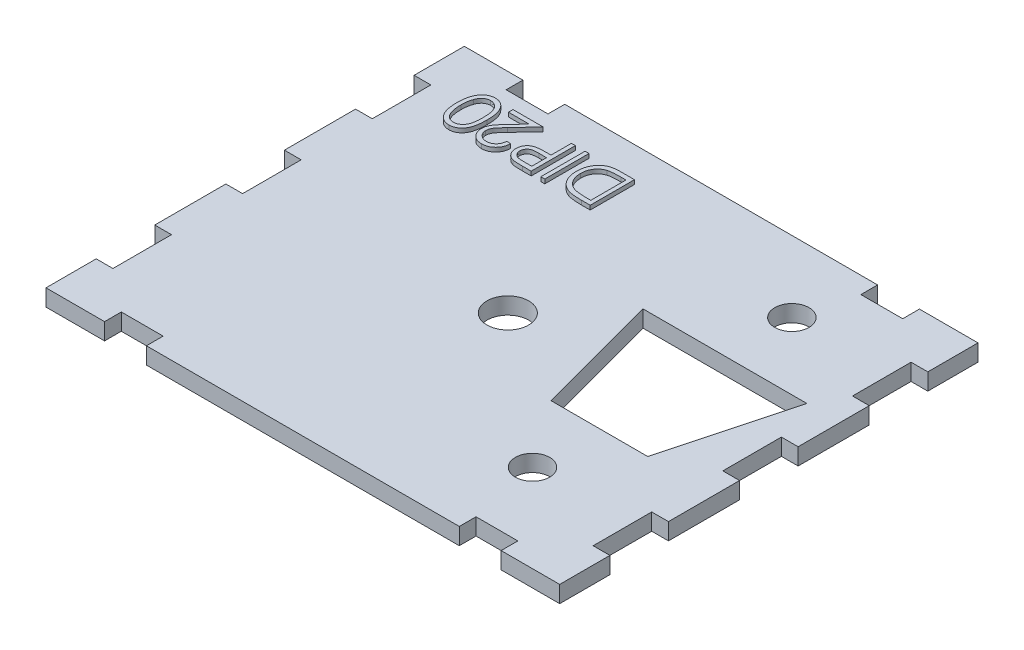
SolidWorks part; units mm, degrees
ref_plane "Front Plane" through (0, 0, 0) normal (0, 0, 1) x (1, 0, 0)
ref_plane "Top Plane" through (0, 0, 0) normal (0, 1, 0) x (1, 0, 0)
ref_plane "Right Plane" through (0, 0, 0) normal (1, 0, 0) x (0, 0, -1)
sketch "Sketch2" plane through (0, 0, 0) normal (0, 1, 0) x (1, 0, 0)
  line L1 (-50, 25) -> (50, 25)
  line L2 (-50, 25) -> (-50, -25)
  line L3 (-50, -25) -> (50, -25)
  line L4 (50, 25) -> (50, -25)
  line L5 (-50, 25) -> (50, -25) construction
  line L6 (-50, -25) -> (50, 25) construction
  point P0 (0, 0)
  dimension "D1" = 100
  dimension "D2" = 50
extrude "Boss-Extrude1" add sketch "Sketch2" along normal blind 2
sketch "Sketch12" plane through (0, 2, 0) normal (0, 1, 0) x (1, 0, 0)
  line L0 (-50, -25) -> (50, -25) construction
  line L1 (-40.2, -25) -> (-50, -25)
  line L2 (-40.2, -25) -> (-40.2, 25)
  line L3 (-40.2, 25) -> (-50, 25)
  line L4 (-50, -25) -> (-50, 25)
  line L5 (-50, -25) -> (50, -25) construction
  line L6 (41.2, -25) -> (50, -25)
  line L7 (41.2, -25) -> (41.2, 25)
  line L8 (41.2, 25) -> (50, 25)
  line L9 (50, -25) -> (50, 25)
extrude "Cut-Extrude8" cut sketch "Sketch12" against normal blind 6
sketch "Sketch13" plane through (0, 2, 0) normal (0, 1, 0) x (1, 0, 0)
  line L1 (-28.2, 19) -> (-30.2, 19)
  line L2 (-28.2, 19) -> (-28.2, 12)
  line L3 (-28.2, 12) -> (-30.2, 12)
  line L4 (-30.2, 19) -> (-30.2, 12)
  line L5 (-28.2, 3.5) -> (-30.2, 3.5)
  line L6 (-28.2, 3.5) -> (-28.2, -3.5)
  line L7 (-28.2, -3.5) -> (-30.2, -3.5)
  line L8 (-30.2, 3.5) -> (-30.2, -3.5)
  line L9 (-28.2, -12) -> (-30.2, -12)
  line L10 (-28.2, -12) -> (-28.2, -19)
  line L11 (-28.2, -19) -> (-30.2, -19)
  line L12 (-30.2, -12) -> (-30.2, -19)
  line L13 (29.2, 19) -> (31.2, 19)
  line L14 (29.2, 19) -> (29.2, 12)
  line L15 (29.2, 12) -> (31.2, 12)
  line L16 (31.2, 19) -> (31.2, 12)
  line L17 (29.2, 3.5) -> (31.2, 3.5)
  line L18 (29.2, 3.5) -> (29.2, -3.5)
  line L19 (29.2, -3.5) -> (31.2, -3.5)
  line L20 (31.2, 3.5) -> (31.2, -3.5)
  line L21 (29.2, -12) -> (31.2, -12)
  line L22 (29.2, -12) -> (29.2, -19)
  line L23 (29.2, -19) -> (31.2, -19)
  line L24 (31.2, -12) -> (31.2, -19)
  line L25 (-40.2, -25) -> (41.2, -25) construction
  line L26 (-23.2, 25) -> (-18.2, 25)
  line L27 (41.2, 25) -> (-40.2, 25) construction
  line L28 (-40.2, -25) -> (41.2, -25) construction
  line L29 (41.2, 25) -> (-40.2, 25) construction
  line L30 (-40.2, -25) -> (41.2, -25) construction
  line L31 (41.2, 25) -> (31.2, 25)
  line L32 (41.2, 25) -> (41.2, -25)
  line L33 (41.2, -25) -> (31.2, -25)
  line L34 (31.2, 25) -> (31.2, -25)
  line L35 (41.2, 25) -> (-40.2, 25) construction
  line L36 (-40.2, -25) -> (-30.2, -25)
  line L37 (-40.2, -25) -> (-40.2, 25)
  line L38 (-40.2, 25) -> (-30.2, 25)
  line L39 (-30.2, -25) -> (-30.2, 25)
  line L40 (-23.2, 25) -> (-23.2, 23)
  line L41 (-23.2, 23) -> (-18.2, 23)
  line L42 (-18.2, 25) -> (-18.2, 23)
  line L43 (-23.2, -25) -> (-18.2, -25)
  line L44 (-23.2, -25) -> (-23.2, -23)
  line L45 (-23.2, -23) -> (-18.2, -23)
  line L46 (-18.2, -25) -> (-18.2, -23)
  line L47 (24.2, -25) -> (19.2, -25)
  line L48 (24.2, -25) -> (24.2, -23)
  line L49 (24.2, -23) -> (19.2, -23)
  line L50 (19.2, -25) -> (19.2, -23)
  line L51 (24.2, 25) -> (19.2, 25)
  line L52 (24.2, 25) -> (24.2, 23)
  line L53 (24.2, 23) -> (19.2, 23)
  line L54 (19.2, 25) -> (19.2, 23)
  point P24 (29.2, 0)
  point P30 (30.2, 3.5)
  line M32 (41.2, -25) -> (41.2, 25)
  line M41 (41.2, 25) -> (-40.2, 25)
  line M42 (-40.2, 25) -> (-40.2, -25)
  line M47 (-40.2, -25) -> (41.2, -25)
  dimension "D1" = 2
  dimension "D2" = 2
  dimension "D3" = 2
  dimension "D4" = 2
  dimension "D5" = 2
  dimension "D6" = 2
  dimension "D7" = 57.4
  dimension "D8" = 57.4
  dimension "D9" = 57.4
  dimension "D10" = 7
  dimension "D11" = 7
  dimension "D12" = 7
  dimension "D13" = 7
  dimension "D14" = 7
  dimension "D15" = 7
  dimension "D16" = 5
  dimension "D17" = 2
  dimension "D18" = 5
  dimension "D19" = 6
  dimension "D20" = 8.5
  dimension "D21" = 8.5
  dimension "D22" = 6
  dimension "D23" = 6
  dimension "D24" = 8.5
  dimension "D25" = 8.5
  dimension "D26" = 6
  dimension "D27" = 5
  dimension "D28" = 5
  dimension "D29" = 2
  dimension "D30" = 2
  dimension "D31" = 5
  dimension "D32" = 5
  dimension "D33" = 5
  dimension "D34" = 5
  dimension "D35" = 2
extrude "Cut-Extrude10" cut sketch "Sketch13" against normal blind 6 contours L5 L8 L7 L6 | L39 L12 L8 L4 M47 M41 M42 | L1 L4 L3 L2 | L50 L48 L49 M47 | L24 L21 L22 L23 | L20 L17 L18 L19 | L16 L13 L14 L15 | L54 L53 L52 M41 | L9 L12 L11 L10 | L34 L16 L20 L24 M41 M47 M32 | L26 L42 L41 L40 | L45 L46 L43 L44
sketch "Sketch15" plane through (0, 0, 0) normal (0, -1, 0) x (1, 0, 0)
  line L0 (24.2, 23) -> (19.2, 23) construction
  line L16 (20.7242, -7.5) -> (20.7242, -8.5)
  line L17 (20.7242, -7.5) -> (25.936, -7.5)
  line L18 (25.936, -7.5) -> (22.4527, 5.5)
  line L19 (22.4527, 5.5) -> (12.4527, 5.5)
  line L20 (12.4527, 5.5) -> (8.9693, -7.5)
  line L21 (8.9693, -7.5) -> (14.1811, -7.5)
  line L22 (14.1811, -7.5) -> (14.1811, -8.5)
  line L23 (14.1811, -8.5) -> (7.6661, -8.5)
  line L24 (7.6661, -8.5) -> (11.6853, 6.5)
  line L25 (11.6853, 6.5) -> (23.22, 6.5)
  line L26 (23.22, 6.5) -> (27.2392, -8.5)
  line L27 (27.2392, -8.5) -> (20.7242, -8.5)
  line L28 (20.7242, -8.5) -> (14.1811, -8.5)
  line L29 (14.1811, -7.5) -> (20.7242, -7.5)
  line L31 (29.2, 12) -> (29.2, 19) construction
  dimension "D4" = 16.5
  dimension "D18" = 11.5347
  dimension "D19" = 15.5291
  dimension "D20" = 15.5291
  dimension "D21" = 13.4586
  dimension "D22" = 13.4586
  dimension "D23" = 10
  dimension "D24" = 5.2118
  dimension "D25" = 5.2118
  dimension "D26" = 6.515
  dimension "D27" = 6.515
  dimension "D28" = 1
  dimension "D29" = 105
  dimension "D30" = 105
  dimension "D31" = 75
  dimension "D32" = 75
  dimension "D33" = 5.98
  dimension "D34" = 1
extrude "Cut-Extrude13" cut sketch "Sketch15" against normal blind 10 contours L21 L29 L17 L18 L19 L20 | L27 L26 L25 L24 L23 L22 L21 L20 L19 L18 L17 L16 | L29 L22 L28 L16
sketch "Sketch16" plane through (0, 0, 0) normal (0, -1, 0) x (-1, 0, 0)
  circle A0 centre (0, 0) radius 2.5
  dimension "D1" = 5
extrude "Cut-Extrude14" cut sketch "Sketch16" against normal blind 10 contours A0
sketch "Sketch17" plane through (0, 0, 0) normal (0, -1, 0) x (-1, 0, 0)
  line L2 (-27.2392, 8.5) -> (-7.6661, 8.5) construction
  line L4 (-11.6853, -6.5) -> (-23.22, -6.5) construction
  circle A0 centre (-17.4527, -14.5) radius 2.05
  circle A1 centre (-17.4527, 16.5) radius 2.05
  dimension "D1" = 4.1
  dimension "D2" = 4.1
  dimension "D3" = 8
  dimension "D4" = 9.7866
  dimension "D5" = 9.7866
  dimension "D6" = 5.7673
  dimension "D7" = 5.7673
  dimension "D8" = 8
extrude "Cut-Extrude15" cut sketch "Sketch17" against normal blind 3.5
sketch "Sketch22" plane through (0, 2, 0) normal (0, 1, 0) x (1, 0, 0)
  line L0 (-24.5837, 20.8621) -> (9.284, 20.8621) construction
  text T0 "DIP20" font "Century Gothic" height in points 20
extrude "Boss-Extrude4" add sketch "Sketch22" along normal blind 0.5
